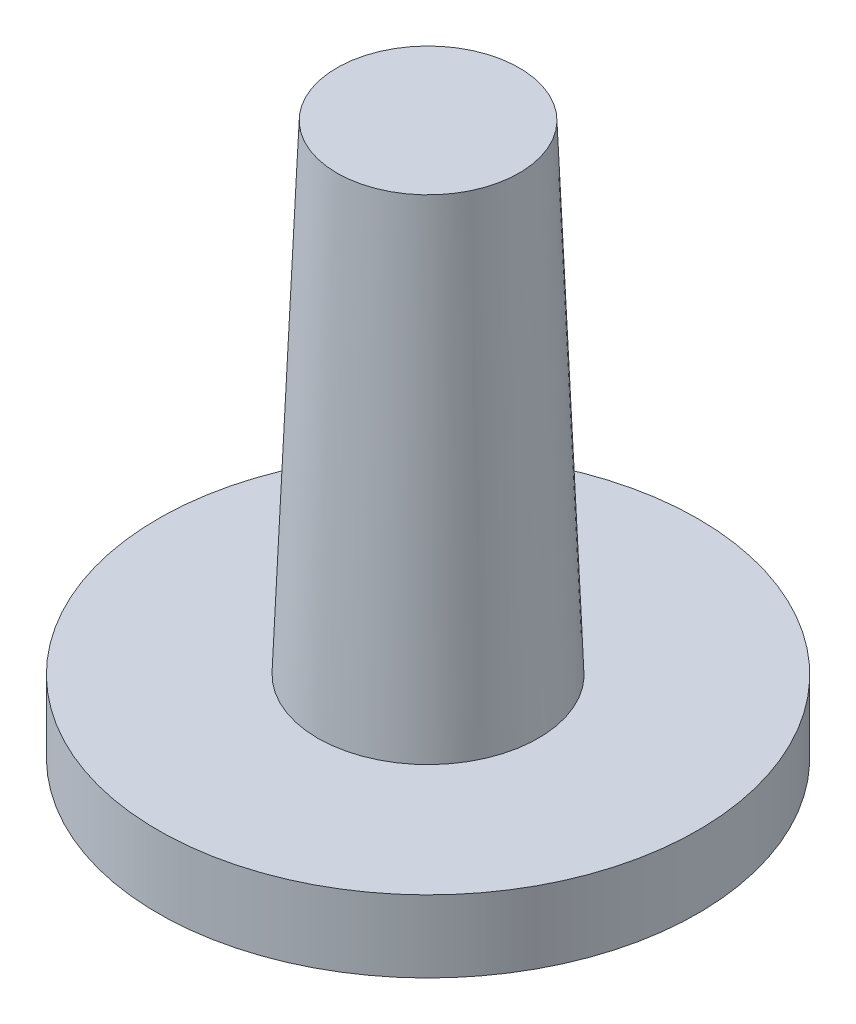
SolidWorks part; units mm, degrees
ref_plane "Front Plane" through (0, 0, 0) normal (0, 0, 1) x (1, 0, 0)
ref_plane "Top Plane" through (0, 0, 0) normal (0, 1, 0) x (1, 0, 0)
ref_plane "Right Plane" through (0, 0, 0) normal (1, 0, 0) x (0, 0, -1)
sketch "Sketch1" plane through (0, 0, 0) normal (0, 1, 0) x (1, 0, 0)
  circle A0 centre (0, 0) radius 3.5719
  dimension "D1" = 7.1438
extrude "Boss-Extrude1" add sketch "Sketch1" along normal blind 0.9525
sketch "Sketch2" plane through (0, 0.9525, 0) normal (0, 1, 0) x (1, 0, 0)
  circle A0 centre (0, 0) radius 3.048
  circle A1 centre (0, 0) radius 1.4605
  dimension "D1" = 6.096
  dimension "D2" = 1.5875
extrude "Boss-Extrude2" add sketch "Sketch2" along normal blind 6.35 contours A1
sketch "Sketch3" plane through (0, 0, 0) normal (1, 0, 0) x (0, 0, -1)
  line L0 (-1.4605, 0.9525) -> (-1.2065, 7.3025)
  line L1 (1.4605, 7.3025) -> (-1.4605, 7.3025) construction
  line L2 (-1.2065, 7.3025) -> (-1.4605, 7.3025)
  line L3 (-1.4605, 7.3025) -> (-1.7383, 7.3025)
  line L4 (-1.7383, 7.3025) -> (-1.4605, 0.9525)
  dimension "D1" = 0.254
ref_axis "Axis1" through (0, 7.3025, 0) along (0, -1, 0)
revolve "Cut-Revolve1" cut sketch "Sketch3" angle 360 about axis through (0, 7.3025, 0) along (0, -1, 0)
